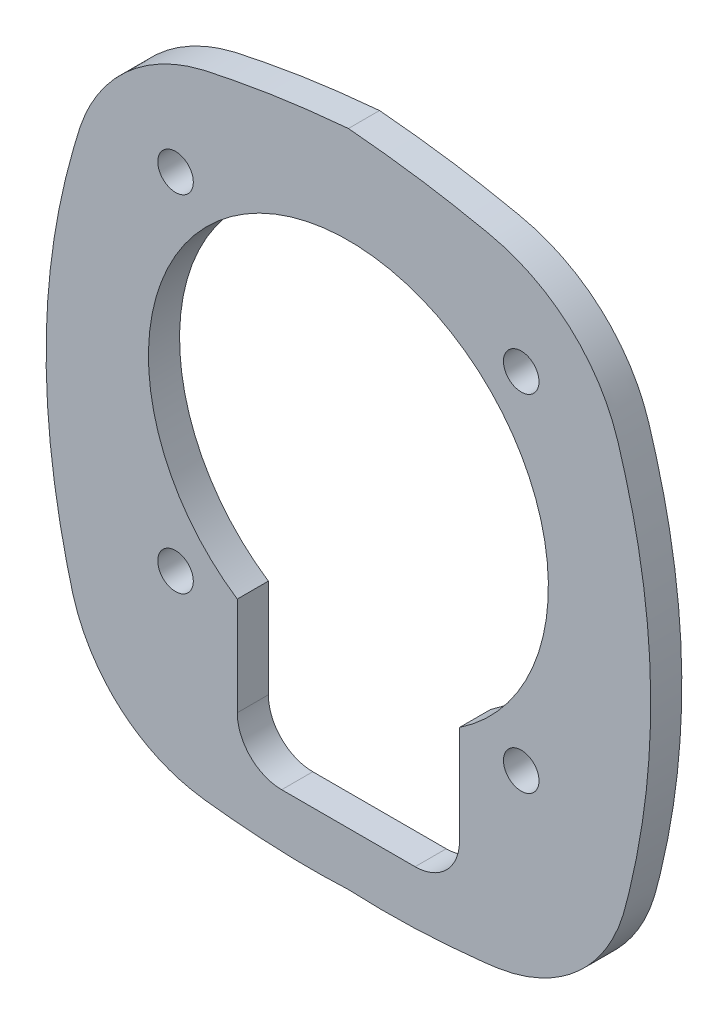
SolidWorks part; units mm, degrees
material "Фанера"
ref_plane "Front Plane" through (0, 0, 0) normal (0, 0, 1) x (1, 0, 0)
ref_plane "Top Plane" through (0, 0, 0) normal (0, 1, 0) x (1, 0, 0)
ref_plane "Right Plane" through (0, 0, 0) normal (1, 0, 0) x (0, 0, -1)
sketch "Эскиз1" plane through (0, 0, 0) normal (0, 0, 1) x (1, 0, 0)
  line L0 (-0.0015, 60.5557) -> (-0.0015, 134.2053) construction
  line L1 (-9.4848, 103.6369) -> (10.8304, 103.6369) construction
  line L6 (-6.0049, 75.812) -> (6.002, 75.812)
  line L7 (-0.0015, 85.6388) -> (0, 85.6369) construction
  line L8 (-0.0015, 85.6351) -> (0, 85.6369) construction
  line L9 (-10.0049, 79.812) -> (-10.0049, 88.6736)
  line L11 (10.002, 79.812) -> (10.002, 88.6716)
  line L12 (-10.0049, 75.812) -> (0.0004, 85.6369) construction
  line L13 (-0.0034, 85.6369) -> (10.002, 75.812) construction
  line L14 (-7.2738, 96.3631) -> (9.1571, 112.794) construction
  arc A0 (6.002, 75.812) -> (10.002, 79.812) centre (6.002, 79.812) ccw
  circle A1 centre (0, 103.6369) radius 4.3081 construction
  arc A2 (10.002, 88.6716) -> (-10.0049, 88.6736) centre (0, 103.6369) ccw
  arc A5 (-6.0049, 75.812) -> (-10.0049, 79.812) centre (-6.0049, 79.812) cw
  arc A6 (-0.0034, 85.6369) -> (0.0004, 85.6369) centre (0, 103.6369) ccw
  circle A7 centre (15.5563, 119.1933) radius 1.6
  circle A8 centre (-15.5593, 119.1933) radius 1.6
  circle A9 centre (15.5563, 88.0806) radius 1.6
  circle A10 centre (-15.5593, 88.0806) radius 1.6
  spline S2 degree 3 poles (0, 71.8315) (0.2244, 71.8205) (0.6841, 71.7981) (1.3906, 71.7739) (2.1299, 71.7565) (3.1203, 71.7448) (4.3408, 71.7502) (6.2668, 71.7976) (8.2168, 71.9045) (10.1384, 72.0606) (11.3175, 72.1756) (12.1908, 72.2722) (12.8055, 72.3427) (13.3777, 72.421) (13.9058, 72.5162) (14.7105, 72.6907) (15.8008, 73.0104) (17.1419, 73.5688) (18.4173, 74.2756) (19.9923, 75.3961) (21.3613, 76.7726) (22.4812, 78.3513) (23.0689, 79.4057) (23.4749, 80.2949) (23.7299, 80.9415) (23.9658, 81.6338) (24.1533, 82.3069) (24.3304, 83.0036) (24.4986, 83.6829) (24.6729, 84.4203) (24.8945, 85.4038) (25.1479, 86.6174) (25.5149, 88.5753) (25.8823, 90.9622) (26.3008, 94.8042) (26.4639, 98.6624) (26.342, 102.5416) (26.1061, 105.4752) (25.7399, 108.3214) (25.2271, 111.2025) (24.5892, 114.0183) (24.0127, 116.1281) (23.5945, 117.5099) (23.393, 118.1622) (23.1446, 118.8493) (22.5789, 120.197) (21.3958, 122.2037) (19.3962, 124.3599) (17.5808, 125.6554) (16.3202, 126.3458) (15.5998, 126.6908) (14.887, 126.9875) (14.1857, 127.2392) (13.4993, 127.4491) (12.8305, 127.6212) (12.1801, 127.7583) (11.2759, 127.9477) (10.1086, 128.1784) (8.6711, 128.4415) (7.236, 128.6816) (5.7947, 128.9003) (4.3525, 129.0967) (2.9098, 129.2708) (1.4615, 129.4257) (0.4914, 129.5118) (0, 129.5554) knots 0 0 0 0 0.007245 0.014841 0.02279 0.031091 0.046775 0.062143 0.093208 0.109725 0.124306 0.131407 0.138054 0.144258 0.150025 0.155351 0.170805 0.186581 0.2021 0.217718 0.248803 0.264075 0.280043 0.287632 0.295585 0.302443 0.311207 0.318104 0.325624 0.333769 0.342538 0.358129 0.373741 0.406766 0.435965 0.498333 0.531062 0.561065 0.593194 0.623552 0.655389 0.686255 0.694049 0.701943 0.708265 0.717598 0.749054 0.782774 0.811662 0.820523 0.829105 0.837402 0.845408 0.85312 0.860537 0.867667 0.874549 0.890325 0.906032 0.92167 0.937239 0.953036 0.968597 0.984095 1 1 1 1 construction
  spline S3 degree 3 poles (0, 129.5554) (-0.3274, 129.5268) (-0.9768, 129.4701) (-1.9414, 129.3741) (-3.0563, 129.2533) (-4.3335, 129.0991) (-5.9304, 128.8821) (-7.6867, 128.6115) (-9.5968, 128.2774) (-11.1065, 127.983) (-12.2257, 127.749) (-12.9657, 127.5909) (-13.7283, 127.3844) (-14.5123, 127.1287) (-15.3133, 126.8172) (-16.1261, 126.4457) (-17.4441, 125.7433) (-19.2803, 124.4583) (-20.8975, 122.7541) (-22.0344, 121.1141) (-22.6475, 120.0027) (-23.0613, 119.0569) (-23.2906, 118.4513) (-23.4514, 117.9742) (-23.5936, 117.5109) (-23.9627, 116.299) (-24.5204, 114.2893) (-25.1661, 111.4983) (-25.6891, 108.6448) (-26.202, 104.8285) (-26.4995, 99.9805) (-26.3292, 95.2328) (-25.9381, 91.395) (-25.5882, 89.016) (-25.2309, 87.0441) (-24.9441, 85.6271) (-24.6298, 84.2176) (-24.3543, 83.096) (-24.1482, 82.29) (-24.0189, 81.8236) (-23.8541, 81.2982) (-23.6443, 80.7117) (-23.262, 79.7982) (-22.7055, 78.7194) (-21.6227, 77.0848) (-20.2754, 75.645) (-18.7079, 74.4633) (-17.4335, 73.7134) (-16.0912, 73.1162) (-14.7298, 72.6834) (-13.29, 72.3869) (-12.0158, 72.2517) (-10.861, 72.1299) (-9.8822, 72.0402) (-8.6902, 71.9441) (-7.3519, 71.8569) (-5.8859, 71.7894) (-4.4312, 71.7513) (-2.9337, 71.7436) (-1.4525, 71.766) (-0.4689, 71.8103) (0, 71.8315) knots 0 0 0 0 0.010598 0.021016 0.031255 0.046759 0.062493 0.083214 0.104054 0.125012 0.132806 0.140921 0.149406 0.158267 0.167501 0.177102 0.187061 0.215635 0.248952 0.262143 0.279925 0.289768 0.295408 0.3008 0.305999 0.311032 0.341649 0.373226 0.403368 0.435154 0.497342 0.559715 0.588091 0.621706 0.637214 0.652703 0.668319 0.683771 0.689942 0.695141 0.699374 0.707697 0.715212 0.731297 0.746741 0.778348 0.794222 0.80993 0.825917 0.841493 0.855899 0.873235 0.88278 0.893344 0.904924 0.92134 0.936583 0.952242 0.968255 0.984867 1 1 1 1 construction
  spline S4 degree 1 poles (0.0005, 130.3585) (-0.0015, 71.0306) knots 0 0 1 1 construction
  spline S5 degree 1 poles (-0.0015, 71.0306) (0.0005, 130.3585) knots 0 0 1 1 construction
  spline S6 degree 3 poles (0.0005, 130.3585) (-1.9455, 130.1885) (-4.8584, 129.8688) (-8.7224, 129.2582) (-11.1223, 128.7926) (-13.0359, 128.4094) (-15.0232, 127.8493) (-17.3518, 126.8009) (-19.874, 125.0131) (-21.9837, 122.7455) (-23.3158, 120.5504) (-24.0971, 118.6337) (-24.6645, 116.74) (-25.3246, 114.3845) (-26.1998, 110.5525) (-26.9602, 105.6954) (-27.3032, 99.7997) (-27.1111, 94.8853) (-26.6923, 90.981) (-26.2473, 88.0692) (-25.7783, 85.667) (-25.339, 83.7483) (-24.996, 82.3391) (-24.576, 80.8596) (-23.7922, 78.961) (-22.4474, 76.7543) (-20.2746, 74.5173) (-17.6592, 72.8344) (-15.2321, 71.9467) (-13.2018, 71.569) (-11.2484, 71.3655) (-8.819, 71.135) (-5.8821, 70.9752) (-2.9406, 70.9249) (-0.9807, 70.9865) (-0.0015, 71.0306) knots -0.000757 -0.000757 -0.000757 -0.000757 0.061765 0.093026 0.124287 0.139918 0.155548 0.186809 0.21807 0.249331 0.280592 0.296223 0.311853 0.343114 0.374376 0.436898 0.49942 0.561942 0.593203 0.624464 0.655725 0.671356 0.686986 0.702617 0.718247 0.749508 0.780769 0.81203 0.843291 0.858922 0.874552 0.905813 0.937074 0.968336 0.999597 0.999597 0.999597 0.999597
  spline S7 degree 3 poles (-0.0015, 71.0306) (1.9571, 70.9351) (4.9047, 70.92) (8.8167, 71.1355) (11.2546, 71.365) (13.1961, 71.5697) (15.2349, 71.9462) (17.6573, 72.8341) (20.2745, 74.5172) (22.4473, 76.7538) (23.7915, 78.96) (24.5757, 80.8579) (24.9949, 82.336) (25.3393, 83.7482) (25.7774, 85.6645) (26.2473, 88.0682) (26.6919, 90.9795) (27.1112, 94.8837) (27.3031, 99.7988) (26.9607, 105.6913) (26.2004, 110.549) (25.3257, 114.3811) (24.6652, 116.7361) (24.0982, 118.6308) (23.3179, 120.5463) (21.9828, 122.7473) (19.8733, 125.0135) (17.3516, 126.8011) (15.0221, 127.8495) (13.0373, 128.4093) (11.1214, 128.7928) (8.7226, 129.2581) (4.8581, 129.8693) (1.946, 130.1859) (0.0005, 130.3585) knots 0.000403 0.000403 0.000403 0.000403 0.062925 0.094187 0.125448 0.141078 0.156709 0.18797 0.219231 0.250492 0.281753 0.297383 0.313014 0.328644 0.344275 0.375536 0.406797 0.438058 0.50058 0.563102 0.625624 0.656886 0.688147 0.703777 0.719408 0.750669 0.78193 0.813191 0.844452 0.860082 0.875713 0.906974 0.938235 1.000757 1.000757 1.000757 1.000757
  point P9 (0, 85.6369)
  dimension "D2" = 36
  dimension "D3" = 4
  dimension "D5" = 3.2
  dimension "D4" = 45
  dimension "D6" = 22
  dimension "D1" = 0.8
extrude "Бобышка-Вытянуть1" add sketch "Эскиз1" along normal mid plane 2.8 contours S6 S7 A9 L6 A5 L9 A2 L11 A0 A7 A8 A10
